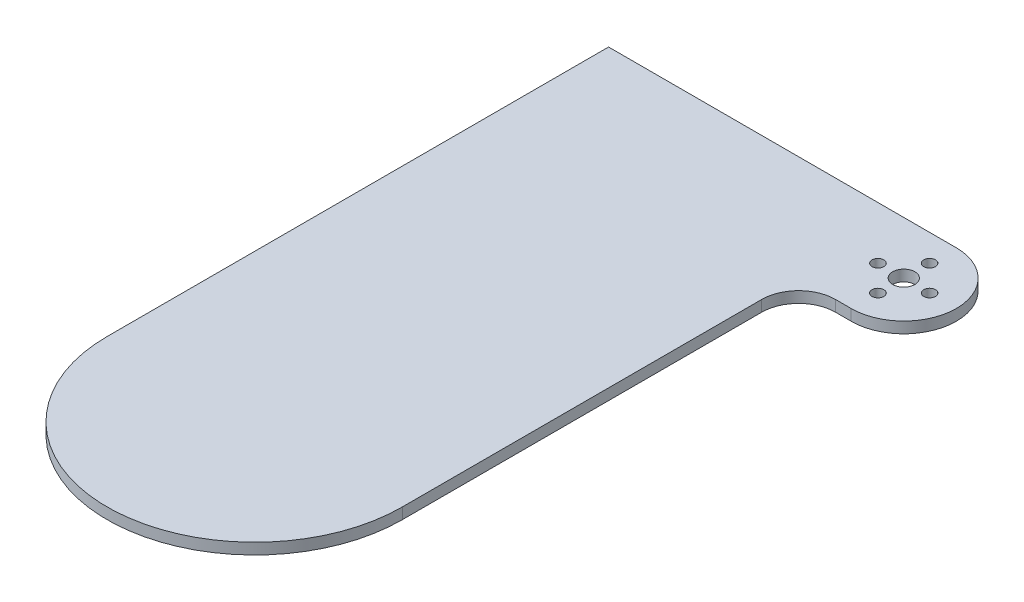
SolidWorks part; units mm, degrees
material "有机玻璃 (TM) GS 丙烯酸铸钣"
ref_plane "前视基准面" through (0, 0, 0) normal (0, 0, 1) x (1, 0, 0)
ref_plane "上视基准面" through (0, 0, 0) normal (0, 1, 0) x (1, 0, 0)
ref_plane "右视基准面" through (0, 0, 0) normal (1, 0, 0) x (0, 0, -1)
sketch "草图1" plane through (0, 0, 0) normal (0, 1, 0) x (1, 0, 0)
  line L0 (-55.5251, -48.4282) -> (-55.5251, 87.4718)
  line L1 (24.4749, -48.4282) -> (24.4749, 48.9718)
  line L2 (38.7249, 87.4718) -> (-55.5251, 87.4718)
  line L3 (38.7249, 58.9718) -> (34.4749, 58.9718)
  arc A0 (-55.5251, -48.4282) -> (24.4749, -48.4282) centre (-15.5251, -48.4282) ccw
  circle A1 centre (38.7249, 73.2218) radius 3
  arc A2 (38.7249, 58.9718) -> (38.7249, 87.4718) centre (38.7249, 73.2218) ccw
  arc A3 (24.4749, 48.9718) -> (34.4749, 58.9718) centre (34.4749, 48.9718) cw
extrude "凸台-拉伸1" add sketch "草图1" along normal blind 3
sketch "草图2" plane through (0, 3, 0) normal (0, 1, 0) x (1, 0, 0)
  circle A0 centre (38.7249, 73.2218) radius 7 construction
  circle A1 centre (38.7249, 80.2218) radius 1.6
  circle A2 centre (45.7249, 73.2218) radius 1.6
  circle A3 centre (38.7249, 66.2218) radius 1.6
  circle A4 centre (31.7249, 73.2218) radius 1.6
  point P14 (38.7249, 73.2218)
  dimension "D1" = 14
  dimension "D2" = 3.2
  dimension "D3" = 4
hole_wizard "Ø3.2 (3.2) 直径孔1" positions "3D草图1" profile "草图3" hole size "Ø3.2" standard "GB" end condition through all
sketch3d "3D草图1"
  point P0 (38.7249, 3, -80.2218)
  point P3 (31.7249, 3, -73.2218)
  point P6 (38.7249, 3, -66.2218)
  point P9 (45.7249, 3, -73.2218)
sketch "草图3" plane through (38.7249, 3, -80.2218) normal (1, 0, 0) x (0, 0, 1)
  line L0 (0, 0) -> (0, 3)
  line L1 (0, 3) -> (1.6, 3)
  line L2 (1.6, 3) -> (1.6, 0)
  line L5 (1.6, 0) -> (0, 0)
  line L11 (0, -6.35) -> (0, 107.95) construction
  dimension "通孔孔直径" = 3.2
  dimension "通孔孔深度" = 3
